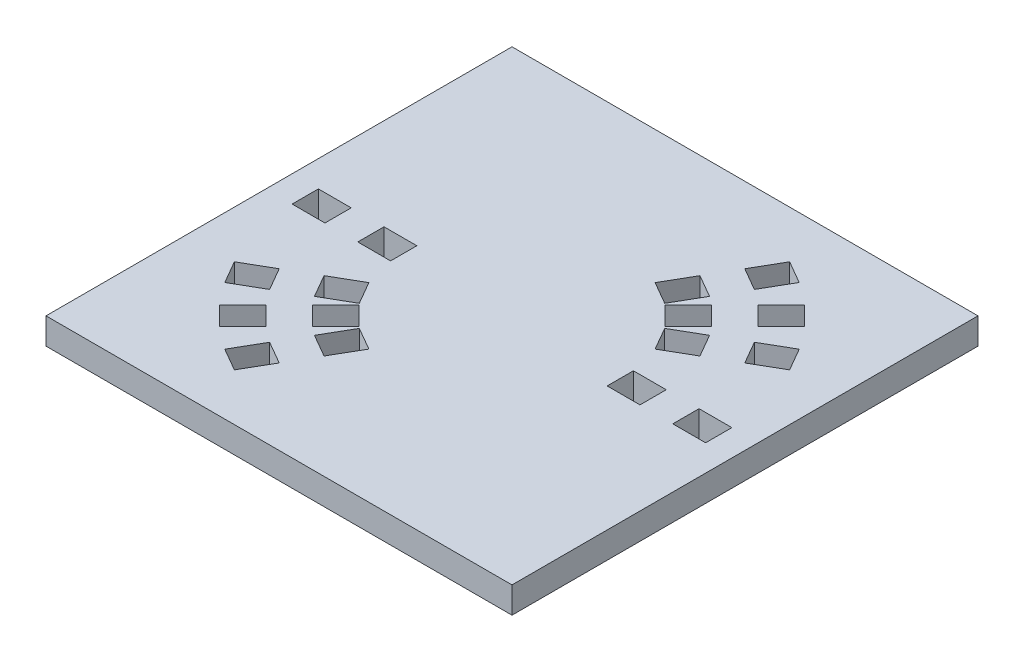
SolidWorks part; units mm, degrees
ref_plane "Front Plane" through (0, 0, 0) normal (0, 0, 1) x (1, 0, 0)
ref_plane "Top Plane" through (0, 0, 0) normal (0, 1, 0) x (1, 0, 0)
ref_plane "Right Plane" through (0, 0, 0) normal (1, 0, 0) x (0, 0, -1)
sketch "Sketch1" plane through (0, 0, 0) normal (0, 1, 0) x (1, 0, 0)
  line L0 (-1.4151, 22.54) -> (-1.4151, -67.6199) construction
  line L1 (-46.495, 22.54) -> (43.6649, 22.54)
  line L2 (-46.495, 22.54) -> (-46.495, -67.6199)
  line L3 (-46.495, -67.6199) -> (43.6649, -67.6199)
  line L4 (43.6649, 22.54) -> (43.6649, -67.6199)
  line L5 (-46.495, -22.54) -> (43.6649, -22.54) construction
  line L6 (-39.3946, -9.7338) -> (-33.261, -11.3773) [skipped]
  line L7 (-41.415, -20) -> (-35.065, -20)
  line L8 (-41.415, -20) -> (-41.415, -25.08)
  line L9 (-41.415, -25.08) -> (-35.065, -25.08)
  line L10 (-35.065, -20) -> (-35.065, -25.08)
  line L11 (-28.715, -20) -> (-22.365, -20)
  line L12 (-28.715, -20) -> (-28.715, -25.08)
  line L13 (-28.715, -25.08) -> (-22.365, -25.08)
  line L14 (-22.365, -20) -> (-22.365, -25.08)
  line L19 (-39.3946, -9.7338) -> (-40.7094, -14.6407) [skipped]
  line L20 (-40.7094, -14.6407) -> (-34.5758, -16.2842) [skipped]
  line L21 (-33.261, -11.3773) -> (-34.5758, -16.2842) [skipped]
  line L22 (-27.1274, -13.0208) -> (-20.9937, -14.6643) [skipped]
  line L23 (-27.1274, -13.0208) -> (-28.4422, -17.9277) [skipped]
  line L24 (-28.4422, -17.9277) -> (-22.3085, -19.5712) [skipped]
  line L25 (-20.9937, -14.6643) -> (-22.3085, -19.5712) [skipped]
  line L30 (-34.786, -0.3403) -> (-29.2868, -3.5153) [skipped]
  line L31 (-34.786, -0.3403) -> (-37.326, -4.7397) [skipped]
  line L32 (-37.326, -4.7397) -> (-31.8268, -7.9147) [skipped]
  line L33 (-29.2868, -3.5153) -> (-31.8268, -7.9147) [skipped]
  line L34 (-23.7875, -6.6903) -> (-18.2882, -9.8653) [skipped]
  line L35 (-23.7875, -6.6903) -> (-26.3275, -11.0897) [skipped]
  line L36 (-26.3275, -11.0897) -> (-20.8282, -14.2647) [skipped]
  line L37 (-18.2882, -9.8653) -> (-20.8282, -14.2647) [skipped]
  line L42 (-27.9032, 7.5403) -> (-23.4131, 3.0502) [skipped]
  line L43 (-27.9032, 7.5403) -> (-31.4953, 3.9482) [skipped]
  line L44 (-31.4953, 3.9482) -> (-27.0052, -0.5419) [skipped]
  line L45 (-23.4131, 3.0502) -> (-27.0052, -0.5419) [skipped]
  line L46 (-18.923, -1.44) -> (-14.4328, -5.9301) [skipped]
  line L47 (-18.923, -1.44) -> (-22.5151, -5.0321) [skipped]
  line L48 (-22.5151, -5.0321) -> (-18.0249, -9.5222) [skipped]
  line L49 (-14.4328, -5.9301) -> (-18.0249, -9.5222) [skipped]
  line L54 (-19.2153, 13.371) -> (-16.0403, 7.8717) [skipped]
  line L55 (-19.2153, 13.371) -> (-23.6147, 10.831) [skipped]
  line L56 (-23.6147, 10.831) -> (-20.4397, 5.3317) [skipped]
  line L57 (-16.0403, 7.8717) -> (-20.4397, 5.3317) [skipped]
  line L58 (-12.8653, 2.3725) -> (-9.6903, -3.1268) [skipped]
  line L59 (-12.8653, 2.3725) -> (-17.2647, -0.1675) [skipped]
  line L60 (-17.2647, -0.1675) -> (-14.0897, -5.6668) [skipped]
  line L61 (-9.6903, -3.1268) -> (-14.0897, -5.6668) [skipped]
  line L66 (-9.3144, 16.7544) -> (-7.6709, 10.6208) [skipped]
  line L67 (-9.3144, 16.7544) -> (-14.2213, 15.4396) [skipped]
  line L68 (-14.2213, 15.4396) -> (-12.5778, 9.306) [skipped]
  line L69 (-7.6709, 10.6208) -> (-12.5778, 9.306) [skipped]
  line L70 (-6.0274, 4.4871) -> (-4.3839, -1.6465) [skipped]
  line L71 (-6.0274, 4.4871) -> (-10.9343, 3.1723) [skipped]
  line L72 (-10.9343, 3.1723) -> (-9.2908, -2.9613) [skipped]
  line L73 (-4.3839, -1.6465) -> (-9.2908, -2.9613) [skipped]
  line L78 (1.1249, 17.46) -> (1.1249, 11.11) [skipped]
  line L79 (1.1249, 17.46) -> (-3.9551, 17.46) [skipped]
  line L80 (-3.9551, 17.46) -> (-3.9551, 11.11) [skipped]
  line L81 (1.1249, 11.11) -> (-3.9551, 11.11) [skipped]
  line L82 (1.1249, 4.76) -> (1.1249, -1.59) [skipped]
  line L83 (1.1249, 4.76) -> (-3.9551, 4.76) [skipped]
  line L84 (-3.9551, 4.76) -> (-3.9551, -1.59) [skipped]
  line L85 (1.1249, -1.59) -> (-3.9551, -1.59) [skipped]
  line L90 (11.3911, 15.4396) -> (9.7476, 9.306) [skipped]
  line L91 (11.3911, 15.4396) -> (6.4842, 16.7544) [skipped]
  line L92 (6.4842, 16.7544) -> (4.8407, 10.6208) [skipped]
  line L93 (9.7476, 9.306) -> (4.8407, 10.6208) [skipped]
  line L94 (8.1041, 3.1723) -> (6.4606, -2.9613) [skipped]
  line L95 (8.1041, 3.1723) -> (3.1972, 4.4871) [skipped]
  line L96 (3.1972, 4.4871) -> (1.5537, -1.6465) [skipped]
  line L97 (6.4606, -2.9613) -> (1.5537, -1.6465) [skipped]
  line L102 (20.7846, 10.831) -> (17.6096, 5.3317)
  line L103 (20.7846, 10.831) -> (16.3852, 13.371)
  line L104 (16.3852, 13.371) -> (13.2102, 7.8717)
  line L105 (17.6096, 5.3317) -> (13.2102, 7.8717)
  line L106 (14.4346, -0.1675) -> (11.2596, -5.6668)
  line L107 (14.4346, -0.1675) -> (10.0352, 2.3725)
  line L108 (10.0352, 2.3725) -> (6.8602, -3.1268)
  line L109 (11.2596, -5.6668) -> (6.8602, -3.1268)
  line L114 (28.6652, 3.9482) -> (24.1751, -0.5419)
  line L115 (28.6652, 3.9482) -> (25.0731, 7.5403)
  line L116 (25.0731, 7.5403) -> (20.583, 3.0502)
  line L117 (24.1751, -0.5419) -> (20.583, 3.0502)
  line L118 (19.6849, -5.0321) -> (15.1948, -9.5222)
  line L119 (19.6849, -5.0321) -> (16.0928, -1.44)
  line L120 (16.0928, -1.44) -> (11.6027, -5.9301)
  line L121 (15.1948, -9.5222) -> (11.6027, -5.9301)
  line L126 (34.4959, -4.7397) -> (28.9966, -7.9147)
  line L127 (34.4959, -4.7397) -> (31.9559, -0.3403)
  line L128 (31.9559, -0.3403) -> (26.4566, -3.5153)
  line L129 (28.9966, -7.9147) -> (26.4566, -3.5153)
  line L130 (23.4974, -11.0897) -> (17.9981, -14.2647)
  line L131 (23.4974, -11.0897) -> (20.9574, -6.6903)
  line L132 (20.9574, -6.6903) -> (15.4581, -9.8653)
  line L133 (17.9981, -14.2647) -> (15.4581, -9.8653)
  line L138 (37.8793, -14.6407) -> (31.7457, -16.2842) [skipped]
  line L139 (37.8793, -14.6407) -> (36.5645, -9.7338) [skipped]
  line L140 (36.5645, -9.7338) -> (30.4309, -11.3773) [skipped]
  line L141 (31.7457, -16.2842) -> (30.4309, -11.3773) [skipped]
  line L142 (25.612, -17.9277) -> (19.4784, -19.5712) [skipped]
  line L143 (25.612, -17.9277) -> (24.2972, -13.0208) [skipped]
  line L144 (24.2972, -13.0208) -> (18.1636, -14.6643) [skipped]
  line L145 (19.4784, -19.5712) -> (18.1636, -14.6643) [skipped]
  line L150 (38.5849, -25.08) -> (32.2349, -25.08)
  line L151 (38.5849, -25.08) -> (38.5849, -20)
  line L152 (38.5849, -20) -> (32.2349, -20)
  line L153 (32.2349, -25.08) -> (32.2349, -20)
  line L154 (25.8849, -25.08) -> (19.5349, -25.08)
  line L155 (25.8849, -25.08) -> (25.8849, -20)
  line L156 (25.8849, -20) -> (19.5349, -20)
  line L157 (19.5349, -25.08) -> (19.5349, -20)
  line L162 (36.5645, -35.3462) -> (30.4309, -33.7027) [skipped]
  line L163 (36.5645, -35.3462) -> (37.8793, -30.4392) [skipped]
  line L164 (37.8793, -30.4392) -> (31.7457, -28.7957) [skipped]
  line L165 (30.4309, -33.7027) -> (31.7457, -28.7957) [skipped]
  line L166 (24.2972, -32.0592) -> (18.1636, -30.4156) [skipped]
  line L167 (24.2972, -32.0592) -> (25.612, -27.1522) [skipped]
  line L168 (25.612, -27.1522) -> (19.4784, -25.5087) [skipped]
  line L169 (18.1636, -30.4156) -> (19.4784, -25.5087) [skipped]
  line L174 (31.9559, -44.7396) -> (26.4566, -41.5646) [skipped]
  line L175 (31.9559, -44.7396) -> (34.4959, -40.3402) [skipped]
  line L176 (34.4959, -40.3402) -> (28.9966, -37.1652) [skipped]
  line L177 (26.4566, -41.5646) -> (28.9966, -37.1652) [skipped]
  line L178 (20.9574, -38.3896) -> (15.4581, -35.2146) [skipped]
  line L179 (20.9574, -38.3896) -> (23.4974, -33.9902) [skipped]
  line L180 (23.4974, -33.9902) -> (17.9981, -30.8152) [skipped]
  line L181 (15.4581, -35.2146) -> (17.9981, -30.8152) [skipped]
  line L186 (25.0731, -52.6202) -> (20.583, -48.1301) [skipped]
  line L187 (25.0731, -52.6202) -> (28.6652, -49.0281) [skipped]
  line L188 (28.6652, -49.0281) -> (24.1751, -44.538) [skipped]
  line L189 (20.583, -48.1301) -> (24.1751, -44.538) [skipped]
  line L190 (16.0928, -43.64) -> (11.6027, -39.1498) [skipped]
  line L191 (16.0928, -43.64) -> (19.6849, -40.0479) [skipped]
  line L192 (19.6849, -40.0479) -> (15.1948, -35.5577) [skipped]
  line L193 (11.6027, -39.1498) -> (15.1948, -35.5577) [skipped]
  line L198 (16.3852, -58.4509) -> (13.2102, -52.9516) [skipped]
  line L199 (16.3852, -58.4509) -> (20.7846, -55.9109) [skipped]
  line L200 (20.7846, -55.9109) -> (17.6096, -50.4116) [skipped]
  line L201 (13.2102, -52.9516) -> (17.6096, -50.4116) [skipped]
  line L202 (10.0352, -47.4524) -> (6.8602, -41.9531) [skipped]
  line L203 (10.0352, -47.4524) -> (14.4346, -44.9124) [skipped]
  line L204 (14.4346, -44.9124) -> (11.2596, -39.4131) [skipped]
  line L205 (6.8602, -41.9531) -> (11.2596, -39.4131) [skipped]
  line L210 (6.4842, -61.8343) -> (4.8407, -55.7007) [skipped]
  line L211 (6.4842, -61.8343) -> (11.3911, -60.5195) [skipped]
  line L212 (11.3911, -60.5195) -> (9.7476, -54.3859) [skipped]
  line L213 (4.8407, -55.7007) -> (9.7476, -54.3859) [skipped]
  line L214 (3.1972, -49.5671) -> (1.5537, -43.4334) [skipped]
  line L215 (3.1972, -49.5671) -> (8.1041, -48.2523) [skipped]
  line L216 (8.1041, -48.2523) -> (6.4606, -42.1186) [skipped]
  line L217 (1.5537, -43.4334) -> (6.4606, -42.1186) [skipped]
  line L222 (-3.9551, -62.5399) -> (-3.9551, -56.1899) [skipped]
  line L223 (-3.9551, -62.5399) -> (1.1249, -62.5399) [skipped]
  line L224 (1.1249, -62.5399) -> (1.1249, -56.1899) [skipped]
  line L225 (-3.9551, -56.1899) -> (1.1249, -56.1899) [skipped]
  line L226 (-3.9551, -49.8399) -> (-3.9551, -43.4899) [skipped]
  line L227 (-3.9551, -49.8399) -> (1.1249, -49.8399) [skipped]
  line L228 (1.1249, -49.8399) -> (1.1249, -43.4899) [skipped]
  line L229 (-3.9551, -43.4899) -> (1.1249, -43.4899) [skipped]
  line L234 (-14.2213, -60.5195) -> (-12.5778, -54.3859) [skipped]
  line L235 (-14.2213, -60.5195) -> (-9.3144, -61.8343) [skipped]
  line L236 (-9.3144, -61.8343) -> (-7.6709, -55.7007) [skipped]
  line L237 (-12.5778, -54.3859) -> (-7.6709, -55.7007) [skipped]
  line L238 (-10.9343, -48.2523) -> (-9.2908, -42.1186) [skipped]
  line L239 (-10.9343, -48.2523) -> (-6.0274, -49.5671) [skipped]
  line L240 (-6.0274, -49.5671) -> (-4.3839, -43.4334) [skipped]
  line L241 (-9.2908, -42.1186) -> (-4.3839, -43.4334) [skipped]
  line L246 (-23.6147, -55.9109) -> (-20.4397, -50.4116)
  line L247 (-23.6147, -55.9109) -> (-19.2153, -58.4509)
  line L248 (-19.2153, -58.4509) -> (-16.0403, -52.9516)
  line L249 (-20.4397, -50.4116) -> (-16.0403, -52.9516)
  line L250 (-17.2647, -44.9124) -> (-14.0897, -39.4131)
  line L251 (-17.2647, -44.9124) -> (-12.8653, -47.4524)
  line L252 (-12.8653, -47.4524) -> (-9.6903, -41.9531)
  line L253 (-14.0897, -39.4131) -> (-9.6903, -41.9531)
  line L258 (-31.4953, -49.0281) -> (-27.0052, -44.538)
  line L259 (-31.4953, -49.0281) -> (-27.9032, -52.6202)
  line L260 (-27.9032, -52.6202) -> (-23.4131, -48.1301)
  line L261 (-27.0052, -44.538) -> (-23.4131, -48.1301)
  line L262 (-22.5151, -40.0479) -> (-18.0249, -35.5577)
  line L263 (-22.5151, -40.0479) -> (-18.923, -43.64)
  line L264 (-18.923, -43.64) -> (-14.4328, -39.1498)
  line L265 (-18.0249, -35.5577) -> (-14.4328, -39.1498)
  line L270 (-37.326, -40.3402) -> (-31.8268, -37.1652)
  line L271 (-37.326, -40.3402) -> (-34.786, -44.7396)
  line L272 (-34.786, -44.7396) -> (-29.2868, -41.5646)
  line L273 (-31.8268, -37.1652) -> (-29.2868, -41.5646)
  line L274 (-26.3275, -33.9902) -> (-20.8282, -30.8152)
  line L275 (-26.3275, -33.9902) -> (-23.7875, -38.3896)
  line L276 (-23.7875, -38.3896) -> (-18.2882, -35.2146)
  line L277 (-20.8282, -30.8152) -> (-18.2882, -35.2146)
  line L282 (-40.7094, -30.4392) -> (-34.5758, -28.7957) [skipped]
  line L283 (-40.7094, -30.4392) -> (-39.3946, -35.3462) [skipped]
  line L284 (-39.3946, -35.3462) -> (-33.261, -33.7027) [skipped]
  line L285 (-34.5758, -28.7957) -> (-33.261, -33.7027) [skipped]
  line L286 (-28.4422, -27.1522) -> (-22.3085, -25.5087) [skipped]
  line L287 (-28.4422, -27.1522) -> (-27.1274, -32.0592) [skipped]
  line L288 (-27.1274, -32.0592) -> (-20.9937, -30.4156) [skipped]
  line L289 (-22.3085, -25.5087) -> (-20.9937, -30.4156) [skipped]
  point P20 (-1.4151, -22.54)
  point P300 (-1.4151, -22.54)
  dimension "D1" = 90.1598
  dimension "D2" = 90.1598
  dimension "D3" = 6.35
  dimension "D4" = 6.35
  dimension "D5" = 6.35
  dimension "D8" = 5.08
  dimension "D9" = 2.54
  dimension "D10" = 5.08
  dimension "D12" = 5.08
  dimension "D14" = 2.54
  dimension "D15" = 24
extrude "Boss-Extrude1" add sketch "Sketch1" along normal blind 5.08
